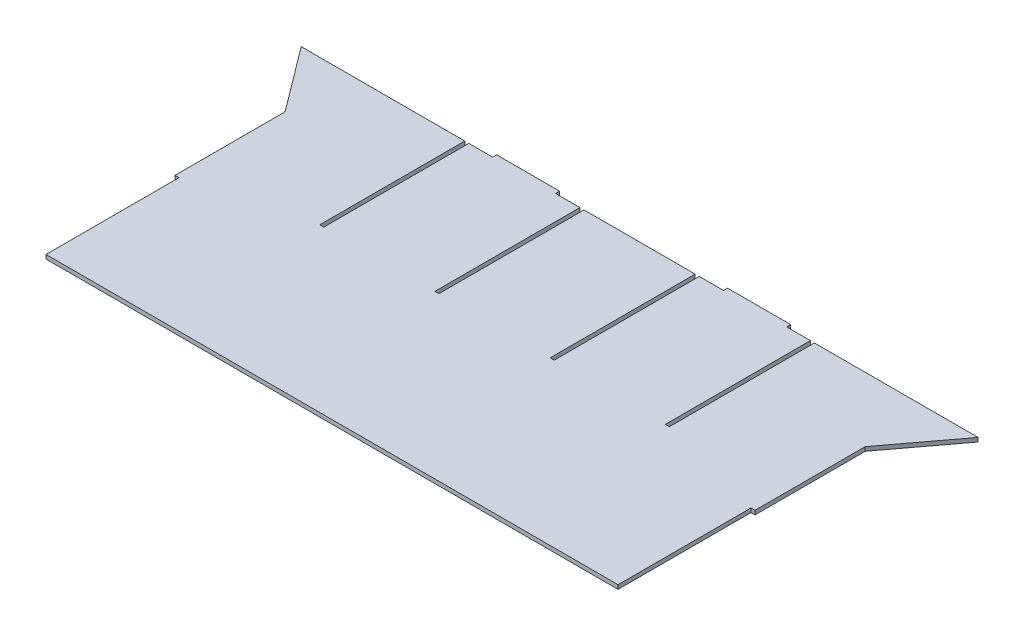
SolidWorks part; units mm, degrees
material "6061-T6 (SS)"
ref_plane "X-Y Datum" through (0, 0, 0) normal (0, 0, 1) x (1, 0, 0)
ref_plane "X-Z Datum" through (0, 0, 0) normal (0, 1, 0) x (1, 0, 0)
ref_plane "Y-Z Datum" through (0, 0, 0) normal (1, 0, 0) x (0, 0, -1)
sketch "Sketch1" plane through (0, 0, 0) normal (0, 0, 1) x (1, 0, 0)
  line L1 (-228.601, -1.5875) -> (228.601, -1.5875)
  line L2 (-228.601, -1.5875) -> (-228.601, 1.5875)
  line L3 (-228.601, 1.5875) -> (228.601, 1.5875)
  line L4 (228.601, -1.5875) -> (228.601, 1.5875)
  line L5 (-228.601, -1.5875) -> (228.601, 1.5875) construction
  line L6 (-228.601, 1.5875) -> (228.601, -1.5875) construction
  point P0 (0, 0)
  dimension "D1" = 3.175
  dimension "D2" = 457.202
extrude "Boss-Extrude1" add sketch "Sketch1" along normal blind 242.425
sketch "Sketch2" plane through (0, 1.5875, 0) normal (0, 1, 0) x (1, 0, 0)
  line L0 (228.601, 0) -> (225.426, 0)
  line L1 (228.601, 0) -> (-228.601, 0) construction
  line L2 (225.426, 0) -> (137.796, 0)
  line L3 (137.796, 0) -> (134.621, 0)
  line L10 (134.621, 0) -> (137.796, 0)
  line L11 (134.621, 0) -> (134.621, -114.3)
  line L12 (134.621, -114.3) -> (137.796, -114.3)
  line L13 (137.796, 0) -> (137.796, -114.3)
  line M2 (228.601, 0) -> (-228.601, 0)
  dimension "D1" = 87.63
  dimension "D2" = 3.175
  dimension "D3" = 114.3
  dimension "D4" = 3.175
extrude "Cut-Extrude1" cut sketch "Sketch2" against normal through all contours L13 L11 L12 M2
pattern_linear "LPattern1" count 4 spacing 90.807 along (-1, 0, 0) of "Cut-Extrude1"
sketch "Sketch3" plane through (0, 0, 0) normal (0, 0, -1) x (-1, 0, 0)
  line L1 (-115.839, 1.5875) -> (-66.1802, 1.5875)
  line L2 (-115.839, 1.5875) -> (-115.839, -1.5875)
  line L3 (-115.839, -1.5875) -> (-66.1802, -1.5875)
  line L4 (-66.1802, 1.5875) -> (-66.1802, -1.5875)
  line L5 (66.2012, 1.5875) -> (115.86, 1.5875)
  line L6 (66.2012, 1.5875) -> (66.2012, -1.5875)
  line L7 (66.2012, -1.5875) -> (115.86, -1.5875)
  line L8 (115.86, 1.5875) -> (115.86, -1.5875)
extrude "Boss-Extrude2" add sketch "Sketch3" along normal blind 3.175
sketch "Sketch4" plane through (0, -1.5875, 0) normal (0, -1, 0) x (1, 0, 0)
  line L0 (-228.601, 0) -> (-266.701, 0)
  line L1 (-266.701, 0) -> (-228.601, 50.8)
  line L2 (-228.601, 242.425) -> (-228.601, 0) construction
  line L3 (-228.601, 50.8) -> (-228.601, 0)
  dimension "D1" = 38.1
  dimension "D2" = 50.8
extrude "Boss-Extrude3" add sketch "Sketch4" against normal blind 3.175
mirror "Mirror1" about plane through (0, 0, 0) normal (1, 0, 0) of "Boss-Extrude3"
sketch "Sketch5" plane through (0, -1.5875, 0) normal (0, -1, 0) x (1, 0, 0)
  line L1 (-228.601, 242.425) -> (-225.426, 242.425)
  line L2 (-228.601, 242.425) -> (-228.601, 137.65)
  line L3 (-228.601, 137.65) -> (-225.426, 137.65)
  line L4 (-225.426, 242.425) -> (-225.426, 137.65)
  dimension "D1" = 3.175
  dimension "D2" = 104.775
extrude "Cut-Extrude2" cut sketch "Sketch5" against normal blind 3.175
mirror "Mirror2" about plane through (0, 0, 0) normal (1, 0, 0) of "Cut-Extrude2"
